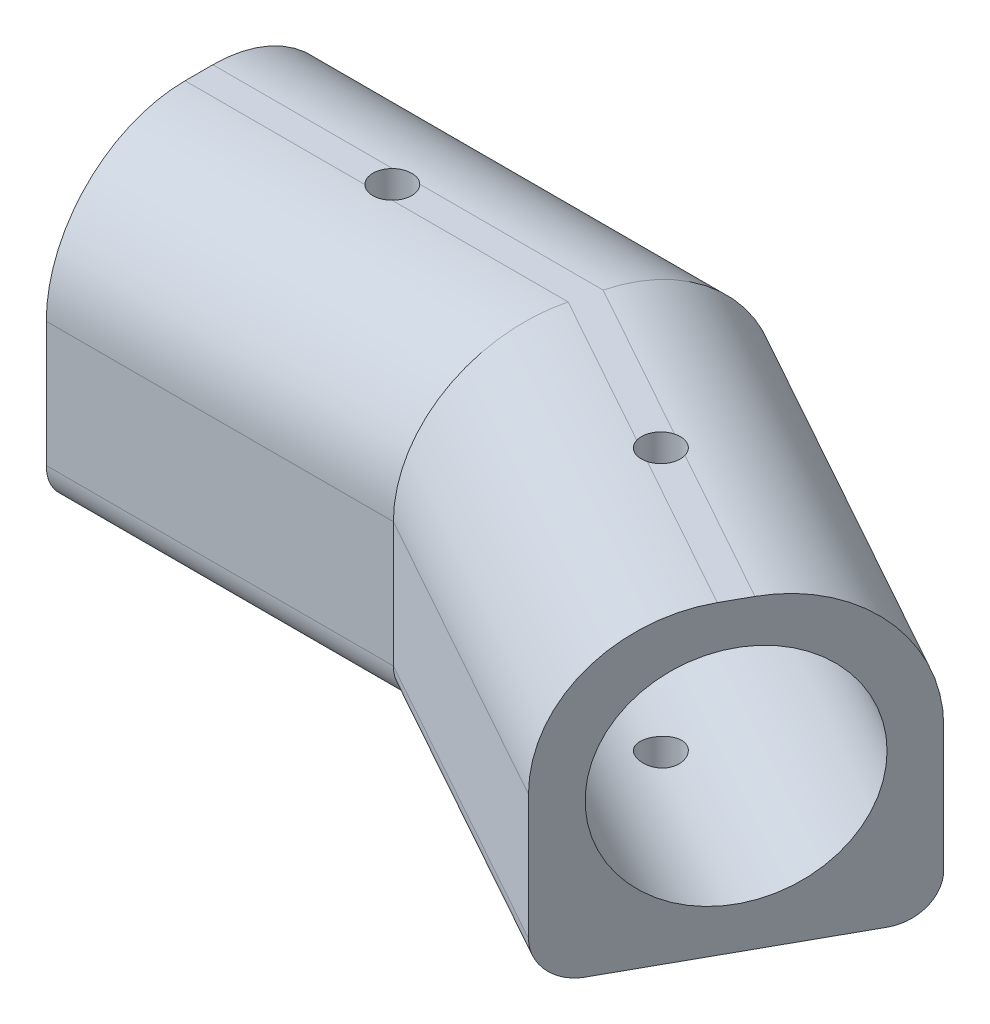
SolidWorks part; units mm, degrees
ref_plane "Front Plane" through (0, 0, 0) normal (0, 0, 1) x (1, 0, 0)
ref_plane "Top Plane" through (0, 0, 0) normal (0, 1, 0) x (1, 0, 0)
ref_plane "Right Plane" through (0, 0, 0) normal (1, 0, 0) x (0, 0, -1)
sketch "Sketch1" plane through (0, 0, 0) normal (0, 1, 0) x (1, 0, 0)
  line L4 (72.9344, -72.9925) -> (83.6097, -53.7562)
  line L5 (-12.5, -13) -> (32.886, -13)
  line L6 (-12.5, -13) -> (78.272, -63.3743)
  line L7 (32.886, -13) -> (-66.6849, -13)
  line L8 (-12.5, -13) -> (-12.5, 0)
  line L9 (-12.5, 0) -> (-12.5, -13)
  line L10 (-12.5, -13) -> (-12.5, -26)
  line L11 (72.9344, -72.9925) -> (-44.555, -7.7913)
  line L12 (32.886, -13) -> (32.886, -26)
  line L13 (83.6097, -53.7562) -> (-19.9131, 3.6943)
  line L14 (32.886, -26) -> (-12.5, -26)
  line L15 (32.886, -13) -> (32.886, 0)
  line L16 (32.886, 0) -> (-12.5, 0)
  line L17 (19.5899, -30.8084) -> (41.4494, -42.9394)
  line L18 (41.4494, -42.9394) -> (36.1117, -52.5576)
  line L19 (36.1117, -52.5576) -> (46.787, -33.3213)
  line L20 (-12.5, -26) -> (-68.7607, -26)
  line L21 (-68.7607, -26) -> (-68.7607, 0)
  line L22 (-68.7607, 0) -> (-12.5, 0)
  line L23 (-12.5, -13) -> (-12.5, -2)
  line L24 (-12.5, -2) -> (-12.5, -13)
  line L25 (-12.5, -13) -> (-12.5, -24)
  line L26 (-12.5, -24) -> (-68.7607, -24)
  line L27 (-68.7607, -24) -> (-68.7607, -2)
  line L28 (-68.7607, -2) -> (32.886, -2)
  line L29 (32.886, -2) -> (32.886, -24)
  line L30 (32.886, -24) -> (-12.5, -24)
extrude "Boss-Extrude3" add sketch "Sketch1" along normal blind 22
sketch "Sketch4" plane through (-68.7607, 0, 0) normal (-1, 0, 0) x (0, 0, 1)
  line L0 (2, 11) -> (24, 11)
  line L1 (2, 22) -> (2, 0) construction
  line L2 (24, 22) -> (24, 0) construction
  circle A0 centre (13, 11) radius 8
extrude "Cut-Extrude4" cut sketch "Sketch4" against normal up to vertex (59.1084 mm away) contours L0 A0 | L0 A0
sketch "Sketch5" plane through (49.9083, 0, 27.6968) normal (0.8744, 0, 0.4852) x (0.4852, 0, -0.8744)
  line L0 (-6.4325, 11) -> (-28.4325, 11)
  line L1 (-6.4325, 22) -> (-6.4325, 0) construction
  line L2 (-28.4325, 22) -> (-28.4325, 0) construction
  circle A0 centre (-17.4325, 11) radius 8
extrude "Cut-Extrude5" cut sketch "Sketch5" against normal up to surface (62.883 mm away) contours A0
sketch "Sketch7" plane through (49.9083, 0, 27.6968) normal (0.8744, 0, 0.4852) x (0.4852, 0, -0.8744)
  circle A0 centre (-17.4325, 11) radius 8 construction
  circle A1 centre (-17.4325, 11) radius 8
extrude "Cut-Extrude6" cut sketch "Sketch7" against normal up to surface (30.7979 mm away)
fillet "Fillet1" radius 10 8 edges at (18.5674, 0, 17.6606) (18.5674, 22, 17.6606) (-39.2065, 0, 2) (-39.2065, 22, 2) (-42.0542, 0, 24) (-42.0542, 22, 24) (10.382, 0, 38.2788) (10.382, 22, 38.2788)
sketch "Sketch9" plane through (-68.7607, 0, 0) normal (-1, 0, 0) x (0, 0, 1)
  line L4 (2, 12) -> (2, 10)
  line L5 (12, 0) -> (14, 0)
  line L6 (24, 10) -> (24, 12)
  line L7 (14, 22) -> (12, 22)
  line L8 (2, 12) -> (2, 10)
  line L9 (12, 0) -> (14, 0)
  line L10 (24, 10) -> (24, 12)
  line L11 (14, 22) -> (12, 22)
  arc A4 (2, 10) -> (12, 0) centre (12, 10) ccw
  arc A5 (14, 0) -> (24, 10) centre (14, 10) ccw
  arc A6 (24, 12) -> (14, 22) centre (14, 12) ccw
  arc A7 (12, 22) -> (2, 12) centre (12, 12) ccw
  arc A8 (2, 10) -> (12, 0) centre (12, 10) ccw
  arc A9 (14, 0) -> (24, 10) centre (14, 10) ccw
  arc A10 (24, 12) -> (14, 22) centre (14, 12) ccw
  arc A11 (12, 22) -> (2, 12) centre (12, 12) ccw
  dimension "D1" = 0
extrude "Cut-Extrude9" cut sketch "Sketch9" against normal blind 28.41
sketch "Sketch10" plane through (49.9083, 0, 27.6968) normal (0.8744, 0, 0.4852) x (0.4852, 0, -0.8744)
  line L4 (-18.4325, 0) -> (-16.4325, 0)
  line L5 (-6.4325, 10) -> (-6.4325, 12)
  line L6 (-16.4325, 22) -> (-18.4325, 22)
  line L7 (-28.4325, 12) -> (-28.4325, 10)
  line L8 (-18.4325, 0) -> (-16.4325, 0)
  line L9 (-6.4325, 10) -> (-6.4325, 12)
  line L10 (-16.4325, 22) -> (-18.4325, 22)
  line L11 (-28.4325, 12) -> (-28.4325, 10)
  arc A4 (-16.4325, 0) -> (-6.4325, 10) centre (-16.4325, 10) ccw
  arc A5 (-6.4325, 12) -> (-16.4325, 22) centre (-16.4325, 12) ccw
  arc A6 (-18.4325, 22) -> (-28.4325, 12) centre (-18.4325, 12) ccw
  arc A7 (-28.4325, 10) -> (-18.4325, 0) centre (-18.4325, 10) ccw
  arc A8 (-16.4325, 0) -> (-6.4325, 10) centre (-16.4325, 10) ccw
  arc A9 (-6.4325, 12) -> (-16.4325, 22) centre (-16.4325, 12) ccw
  arc A10 (-18.4325, 22) -> (-28.4325, 12) centre (-18.4325, 12) ccw
  arc A11 (-28.4325, 10) -> (-18.4325, 0) centre (-18.4325, 10) ccw
  dimension "D1" = 0
extrude "Cut-Extrude10" cut sketch "Sketch10" against normal blind 33.85
sketch "Sketch11" plane through (0, 0, 0) normal (0, -1, 0) x (1, 0, 0)
  line L0 (-40.3507, 24) -> (-40.3507, 2)
  line L1 (-40.3507, 2) -> (-9.6523, 2)
  line L2 (-9.6523, 2) -> (17.1893, 16.8958)
  line L3 (17.1893, 16.8958) -> (6.514, 36.1322)
  line L4 (6.514, 36.1322) -> (-15.3477, 24)
  line L5 (-15.3477, 24) -> (-40.3507, 24)
  line L6 (-40.3507, 13) -> (-12.5, 13)
  line L7 (-12.5, 13) -> (11.8516, 26.514)
  line L8 (-15.3477, 24) -> (-12.5, 13)
  line M9 (-12.7589, 14) -> (-40.3507, 14)
extrude "Boss-Extrude4" add sketch "Sketch11" against normal up to surface contours L8 L5 L0 M9 up to face at (-27.336, 3.9645, 20.0355)
sketch "Sketch12" plane through (0, 0, 0) normal (0, -1, 0) x (1, 0, 0)
  line L0 (-15.3477, 24) -> (6.514, 36.1322)
  line L1 (6.514, 36.1322) -> (11.8516, 26.514)
  line L2 (11.3664, 27.3884) -> (12.3369, 25.6397) construction
  line L3 (11.8516, 26.514) -> (-17.0563, 10.4715)
  line L4 (-17.0563, 10.4715) -> (-15.3477, 24)
  line L5 (-15.3477, 24) -> (-12.7589, 14)
  line L6 (-12.7589, 14) -> (-9.6523, 2)
  line L7 (-9.6523, 2) -> (-12.5, 13)
  line M2 (11.3664, 27.3884) -> (-12.7589, 14)
  line M3 (-12.7589, 14) -> (-15.3477, 24)
extrude "Boss-Extrude5" add sketch "Sketch12" against normal up to surface contours L1 L0 M3 M2 up to face at (-2.9418, 3.9645, 26.3506)
sketch "Sketch13" plane through (0, 0, 0) normal (0, -1, 0) x (1, 0, 0)
  line L0 (-40.3507, 12) -> (-12.2411, 12)
  line L1 (-12.2411, 12) -> (-9.6523, 2)
  line L2 (-9.6523, 2) -> (-40.3507, 2)
  line L3 (-40.3507, 2) -> (-40.3507, 12)
extrude "Boss-Extrude6" add sketch "Sketch13" against normal up to surface (10 mm away)
sketch "Sketch14" plane through (0, 0, 0) normal (0, -1, 0) x (1, 0, 0)
  line L0 (-12.2411, 12) -> (12.3369, 25.6397)
  line L1 (12.3369, 25.6397) -> (17.1893, 16.8958)
  line L2 (17.1893, 16.8958) -> (-9.6523, 2)
  line L3 (-9.6523, 2) -> (-12.2411, 12)
extrude "Boss-Extrude7" add sketch "Sketch14" against normal up to surface (10 mm away)
sketch "Sketch15" plane through (0, 0, 0) normal (0, -1, 0) x (1, 0, 0)
  line L0 (-40.3507, 13) -> (-0.6076, 13)
  line L1 (-40.3507, 2) -> (-40.3507, 24) construction
  line L2 (-0.6076, 13) -> (11.8516, 26.514)
  line L3 (6.514, 36.1322) -> (17.1893, 16.8958) construction
  line L4 (11.8516, 26.514) -> (-12.5, 13)
  line L5 (-14.571, 21) -> (-12.5, 13) construction
  line L6 (-12.5, 13) -> (-40.3507, 13)
  circle A0 centre (-26.4253, 13) radius 1.4
  circle A1 centre (-0.3242, 19.757) radius 1.4
extrude "Cut-Extrude11" cut sketch "Sketch15" against normal blind 40 contours L6 A0 | L6 A0 | L4 A1 | L4 A1
fillet "Fillet2" radius 3 4 edges at (-25.0015, 0, 2) (3.7685, 0, 9.4479) (-4.4169, 0, 30.0661) (-27.8492, 0, 24)
